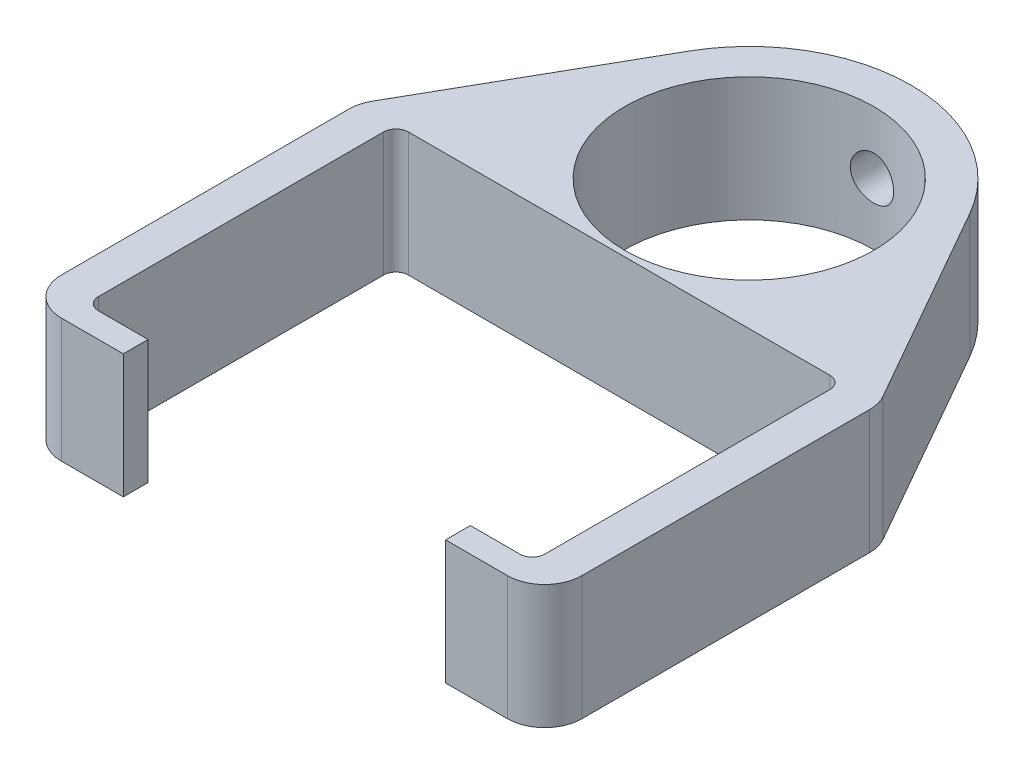
SolidWorks part; units mm, degrees
ref_plane "前视基准面" through (0, 0, 0) normal (0, 0, 1) x (1, 0, 0)
ref_plane "上视基准面" through (0, 0, 0) normal (0, 1, 0) x (1, 0, 0)
ref_plane "右视基准面" through (0, 0, 0) normal (1, 0, 0) x (0, 0, -1)
sketch "草图1" plane through (0, 0, 0) normal (0, 1, 0) x (1, 0, 0)
  line L0 (-21, -10.5) -> (21, -10.5)
  line L1 (0, -21) -> (0, 0) construction
  line L2 (-21, -10.5) -> (-11.3393, 6.4593)
  line L3 (21, -10.5) -> (11.3393, 6.4593)
  line L5 (-21, -10.5) -> (-18, -10.5)
  line L6 (-21, -10.5) -> (-21, -37.5)
  line L7 (-21, -37.5) -> (-18, -37.5)
  line L8 (-18, -10.5) -> (-18, -37.5)
  line L9 (21, -10.5) -> (18, -10.5)
  line L10 (21, -10.5) -> (21, -37.5)
  line L11 (21, -37.5) -> (18, -37.5)
  line L12 (18, -10.5) -> (18, -37.5)
  line L13 (-18, -37.5) -> (-13, -37.5)
  line L14 (-18, -37.5) -> (-18, -35.5)
  line L15 (-18, -35.5) -> (-13, -35.5)
  line L16 (-13, -37.5) -> (-13, -35.5)
  line L17 (18, -37.5) -> (13, -37.5)
  line L18 (18, -37.5) -> (18, -35.5)
  line L19 (18, -35.5) -> (13, -35.5)
  line L20 (13, -37.5) -> (13, -35.5)
  circle A0 centre (0, 0) radius 10.05
  arc A1 (7.7494, -10.5) -> (-7.7494, -10.5) centre (0, 0) ccw
  point P10 (0, -10.5)
  dimension "D1" = 20.1
  dimension "D2" = 3
  dimension "D3" = 42
  dimension "D4" = 10.5
  dimension "D5" = 3
  dimension "D6" = 27
  dimension "D7" = 2
  dimension "D8" = 5
extrude "凸台-拉伸1" add sketch "草图1" along normal blind 10
fillet "圆角1" radius 3 4 edges at (21, 5, 37.5) (-21, 5, 37.5) (21, 5, 10.5) (-21, 5, 10.5)
fillet "圆角2" radius 1 4 edges at (18, 5, 35.5) (18, 5, 10.5) (-18, 5, 35.5) (-18, 5, 10.5)
sketch "草图2" plane through (0, 0, 0) normal (0, 0, 1) x (1, 0, 0)
  line L0 (0, 5) -> (0, 0) construction
  circle A0 centre (0, 5) radius 1.75
  dimension "D2" = 3.5
  dimension "D1" = 5
extrude "切除-拉伸1" cut sketch "草图2" against normal through all
